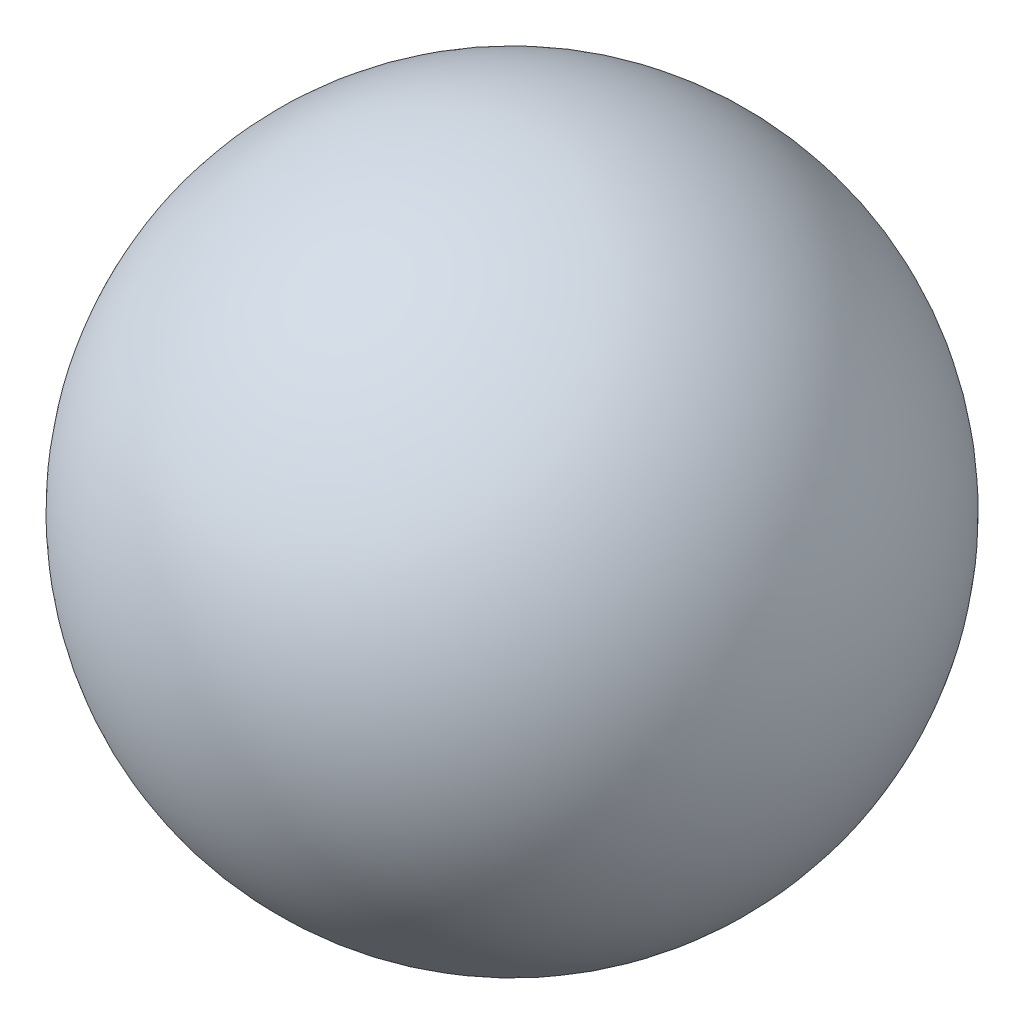
SolidWorks part; units mm, degrees
ref_plane "Top" through (0, 0, 0) normal (0, 0, 1) x (1, 0, 0)
ref_plane "Front" through (0, 0, 0) normal (0, 1, 0) x (1, 0, 0)
ref_plane "Right" through (0, 0, 0) normal (1, 0, 0) x (0, 0, -1)
sketch "Sketch1" plane through (0, 0, 0) normal (0, 0, 1) x (1, 0, 0)
  line L0 (0, 0) -> (12.7, 0) construction
  line L1 (12.7, 0) -> (-12.7, 0) construction
  line L2 (12.7, 0) -> (-12.7, 0)
  arc A1 (12.7, 0) -> (-12.7, 0) centre (0, 0) ccw
  dimension "D1" = 25.4
revolve "Revolve1" add sketch "Sketch1" angle 360 about L2
